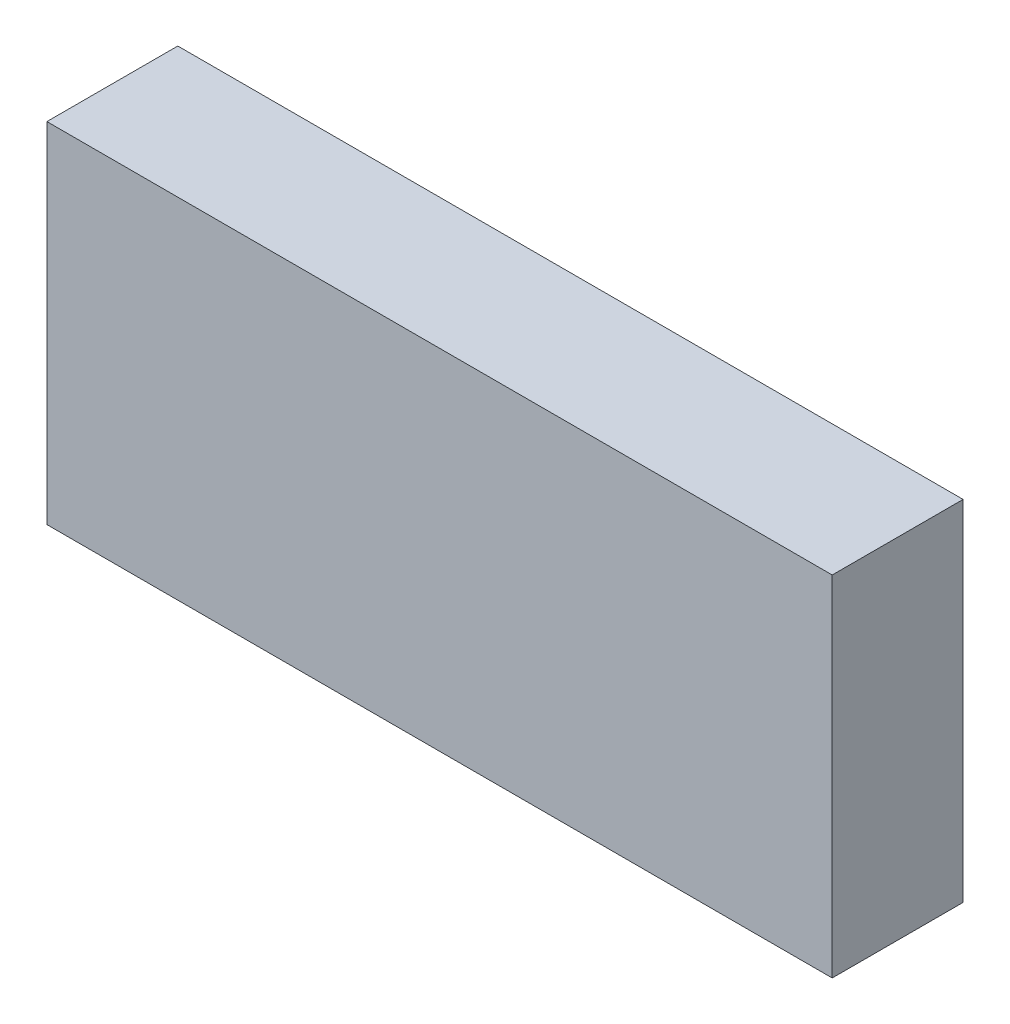
SolidWorks part; units mm, degrees
material "7075-T6, Plate (SS)"
ref_plane "Front Plane" through (0, 0, 0) normal (0, 0, 1) x (1, 0, 0)
ref_plane "Top Plane" through (0, 0, 0) normal (0, 1, 0) x (1, 0, 0)
ref_plane "Right Plane" through (0, 0, 0) normal (1, 0, 0) x (0, 0, -1)
sketch "Sketch1" plane through (0, 0, 0) normal (0, 0, 1) x (1, 0, 0)
  line L1 (0, 0) -> (900, 0)
  line L2 (0, 0) -> (0, 400)
  line L3 (0, 400) -> (900, 400)
  line L4 (900, 0) -> (900, 400)
  dimension "Length" = 900
  dimension "Width" = 400
extrude "Boss-Extrude1" add sketch "Sketch1" along normal blind 150
